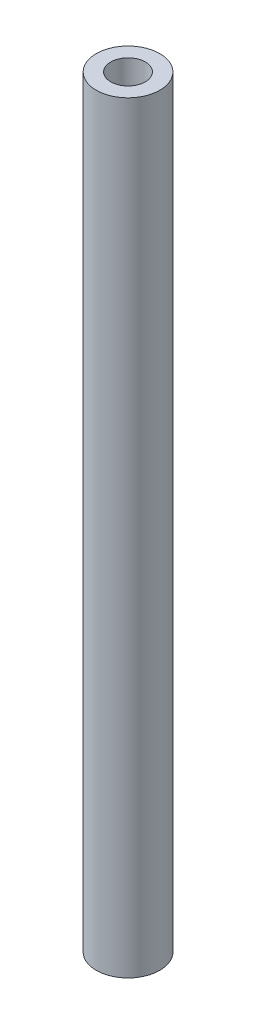
SolidWorks part; units mm, degrees
ref_plane "Front Plane" through (0, 0, 0) normal (0, 0, 1) x (1, 0, 0)
ref_plane "Top Plane" through (0, 0, 0) normal (0, 1, 0) x (1, 0, 0)
ref_plane "Right Plane" through (0, 0, 0) normal (1, 0, 0) x (0, 0, -1)
sketch "Sketch1" plane through (0, 0, 0) normal (0, 1, 0) x (1, 0, 0)
  circle A0 centre (0, 0) radius 3.175
  dimension "D1" = 6.35
extrude "Boss-Extrude1" add sketch "Sketch1" along normal blind 76.2
hole_wizard "#8-32 Tapped Hole1" positions "Sketch3" profile "Sketch2" tap size "#8-32" standard "ANSI Inch"
sketch "Sketch3" plane through (0, 76.2, 0) normal (0, 1, 0) x (1, 0, 0)
  point P0 (0, 0)
sketch "Sketch2" plane through (0, 76.2, 0) normal (1, 0, 0) x (0, 0, 1)
  line L0 (0, 0) -> (0, 11.0378)
  line L1 (0, 11.0378) -> (1.7272, 10)
  line L2 (1.7272, 10) -> (1.7272, 0)
  line L5 (1.7272, 0) -> (0, 0)
  line L10 (0, 11.0378) -> (-1.7272, 10) construction
  line L11 (0, -6.35) -> (0, 107.95) construction
  dimension "Tap Drill Dia." = 3.4544
  dimension "Tap Drill Depth" = 10
  dimension "Drill Angle" = 118
cosmetic thread "Hole Thread1" parameters "D1"=10, "D2"=4.1656
hole_wizard "#8-32 Tapped Hole2" positions "Sketch5" profile "Sketch4" tap size "#8-32" standard "ANSI Inch"
sketch "Sketch5" plane through (0, 0, 0) normal (0, -1, 0) x (-1, 0, 0)
  point P0 (0, 0)
sketch "Sketch4" plane through (0, 0, 0) normal (1, 0, 0) x (0, 0, -1)
  line L0 (0, 0) -> (0, 11.0378)
  line L1 (0, 11.0378) -> (1.7272, 10)
  line L2 (1.7272, 10) -> (1.7272, 0)
  line L5 (1.7272, 0) -> (0, 0)
  line L10 (0, 11.0378) -> (-1.7272, 10) construction
  line L11 (0, -6.35) -> (0, 107.95) construction
  dimension "Tap Drill Dia." = 3.4544
  dimension "Tap Drill Depth" = 10
  dimension "Drill Angle" = 118
cosmetic thread "Hole Thread2" parameters "D1"=10, "D2"=4.1656
